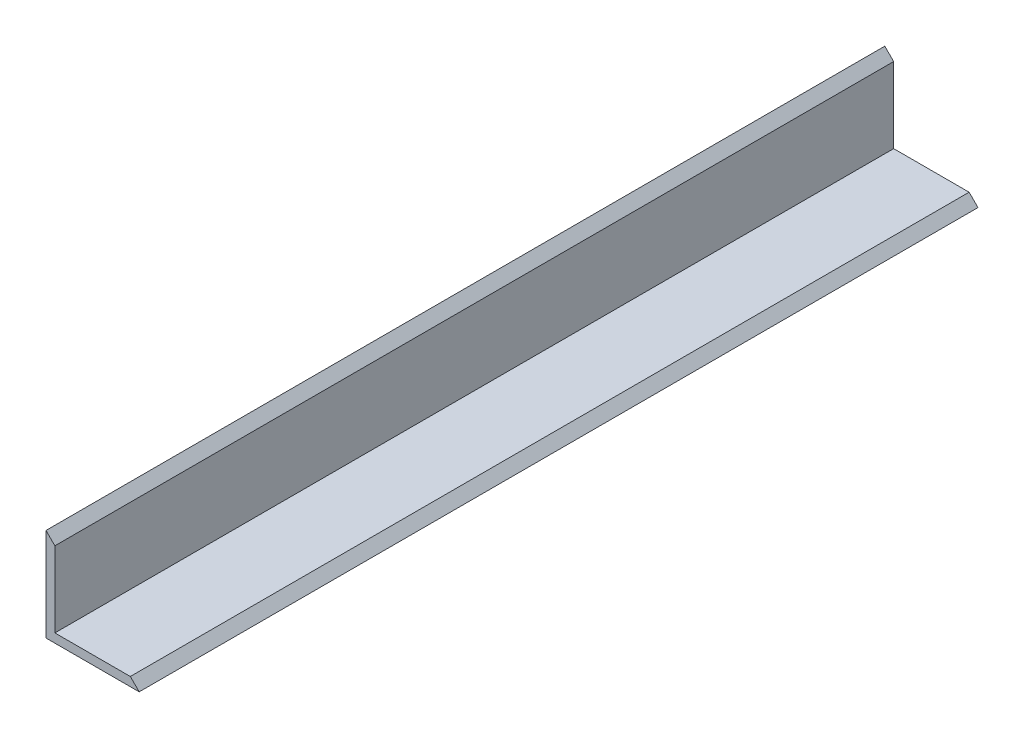
SolidWorks part; units mm, degrees
material "Alloy Steel"
ref_plane "Front Plane" through (0, 0, 0) normal (0, 0, 1) x (1, 0, 0)
ref_plane "Top Plane" through (0, 0, 0) normal (0, 1, 0) x (1, 0, 0)
ref_plane "Right Plane" through (0, 0, 0) normal (1, 0, 0) x (0, 0, -1)
sketch "Sketch1" plane through (0, 0, 0) normal (0, 0, 1) x (1, 0, 0)
  line L0 (0, 100) -> (0, 0) construction
  line L1 (0, 0) -> (100, 0) construction
  line L2 (-5, 100) -> (-5, -5)
  line L3 (-5, -5) -> (100, -5)
  line L4 (5, 100) -> (5, 5)
  line L5 (5, 5) -> (100, 5)
  line L6 (-5, 100) -> (5, 100)
  line L7 (100, -5) -> (100, 5)
  dimension "D1" = 100
  dimension "D2" = 100
  dimension "D3" = 5
  dimension "D4" = 5
extrude "Boss-Extrude1" add sketch "Sketch1" along normal blind 945
sketch "Sketch2" plane through (0, 0, 945) normal (0, 0, 1) x (1, 0, 0)
  line L0 (-5, 100) -> (100, -5)
  line L1 (-5, 100) -> (5, 100)
  line L2 (5, 100) -> (100, 5)
  line L3 (100, 5) -> (5, 5) construction
  line L4 (100, -5) -> (100, 5) construction
  line L5 (100, 5) -> (100, -5)
extrude "Cut-Extrude1" cut sketch "Sketch2" against normal through all
